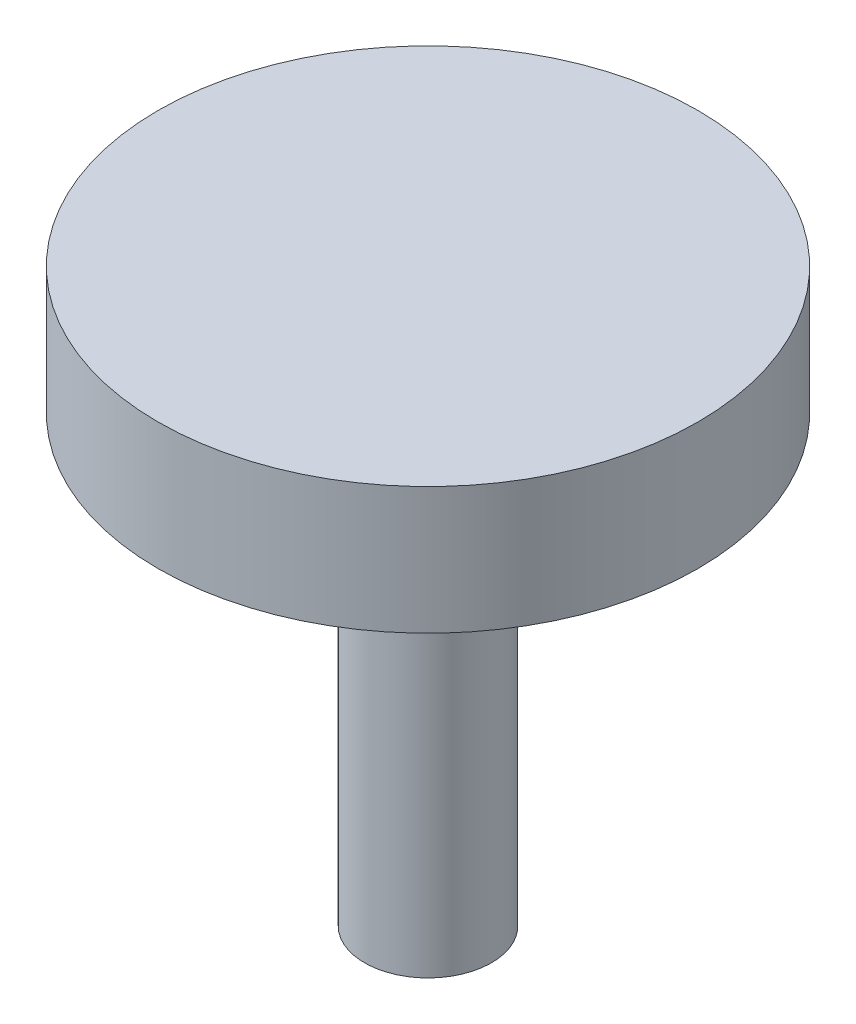
SolidWorks part; units mm, degrees
ref_plane "前基準面" through (0, 0, 0) normal (0, 0, 1) x (1, 0, 0)
ref_plane "上基準面" through (0, 0, 0) normal (0, 1, 0) x (1, 0, 0)
ref_plane "右基準面" through (0, 0, 0) normal (1, 0, 0) x (0, 0, -1)
sketch "草圖1" plane through (0, 0, 0) normal (0, 1, 0) x (1, 0, 0)
  circle A0 centre (0, 0) radius 42.5
  dimension "D1" = 85
extrude "填料-伸長1" add sketch "草圖1" along normal blind 20
sketch "草圖2" plane through (0, 0, 0) normal (0, -1, 0) x (1, 0, 0)
  circle A0 centre (0, 0) radius 10
  dimension "D1" = 20
extrude "填料-伸長2" add sketch "草圖2" along normal blind 70
